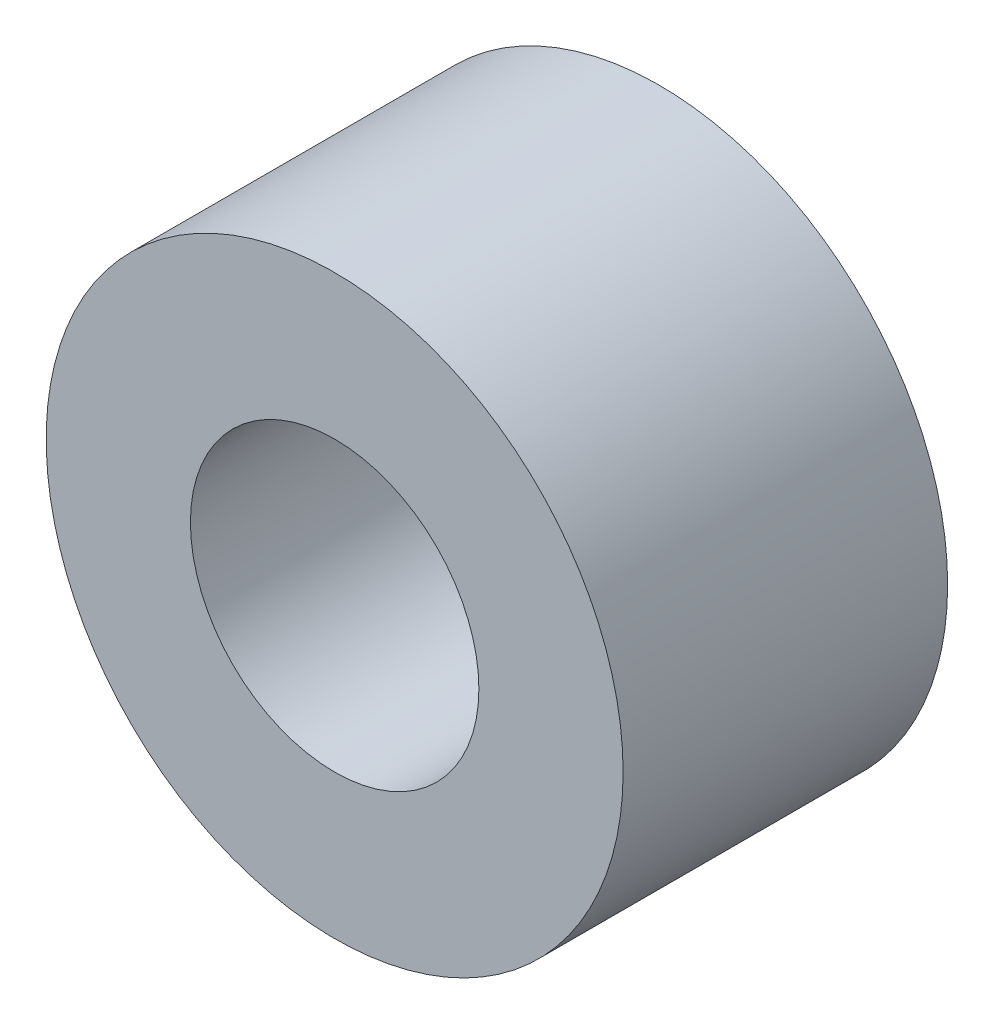
SolidWorks part; units mm, degrees
material "Plain Carbon Steel"
ref_plane "Front Plane" through (0, 0, 0) normal (0, 0, 1) x (1, 0, 0)
ref_plane "Top Plane" through (0, 0, 0) normal (0, 1, 0) x (1, 0, 0)
ref_plane "Right Plane" through (0, 0, 0) normal (1, 0, 0) x (0, 0, -1)
sketch "Sketch1" plane through (0, 0, 0) normal (0, 0, 1) x (1, 0, 0)
  circle A0 centre (0, 0) radius 6.35
  dimension "D1" = 12.7
extrude "Boss-Extrude1" add sketch "Sketch1" along normal blind 7.1437
sketch "Sketch2" plane through (0, 0, 7.1437) normal (0, 0, 1) x (1, 0, 0)
  circle A0 centre (0, 0) radius 3.175
  dimension "D1" = 6.35
extrude "Cut-Extrude1" cut sketch "Sketch2" against normal through all
